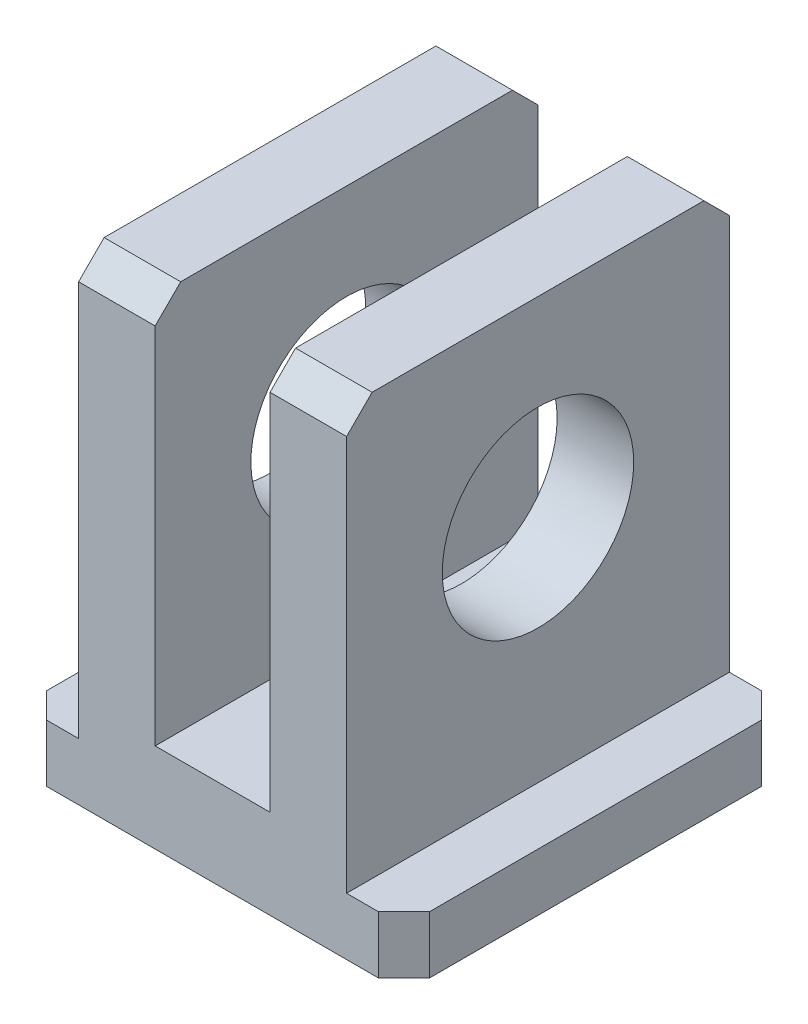
SolidWorks part; units mm, degrees
ref_plane "前视基准面" through (0, 0, 0) normal (0, 0, 1) x (1, 0, 0)
ref_plane "上视基准面" through (0, 0, 0) normal (0, 1, 0) x (1, 0, 0)
ref_plane "右视基准面" through (0, 0, 0) normal (1, 0, 0) x (0, 0, -1)
other "Configuration Table"
sketch "草图1" plane through (0, 0, 0) normal (0, 1, 0) x (1, 0, 0)
  line L0 (-15, 13) -> (-13, 15)
  line L1 (-13, -15) -> (13, -15)
  line L2 (-15, -13) -> (-15, 13)
  line L3 (-13, 15) -> (13, 15)
  line L4 (15, -13) -> (15, 13)
  line L5 (-15, -15) -> (15, 15) construction
  line L6 (-15, 15) -> (15, -15) construction
  line L7 (13, 15) -> (15, 13)
  line L8 (13, -15) -> (15, -13)
  line L9 (-15, -13) -> (-13, -15)
  point P0 (0, 0)
  dimension "D1" = 30
  dimension "D2" = 30
extrude "凸台-拉伸1" add sketch "草图1" along normal blind 4.5
sketch "草图2" plane through (15, 0, 0) normal (1, 0, 0) x (0, 0, -1)
  line L0 (-15, 4.5) -> (-15, 35.5)
  line L1 (-13, 37.5) -> (13, 37.5)
  line L2 (15, 4.5) -> (15, 35.5)
  line L3 (-15, 35.5) -> (-13, 37.5)
  line L4 (15, 35.5) -> (13, 37.5)
  line L5 (-15, 4.5) -> (15, 4.5)
  point P1 (-15, 37.5)
  point P5 (15, 37.5)
  dimension "D1" = 33
extrude "凸台-拉伸2" add sketch "草图2" against normal blind 30
sketch "草图3" plane through (0, 0, 15) normal (0, 0, 1) x (1, 0, 0)
  line L0 (-15, 4.5) -> (-10.5, 4.5)
  line L1 (-10.5, 4.5) -> (-10.5, 37.5)
  line L2 (-15, 37.5) -> (15, 37.5) construction
  line L3 (-15, 4.5) -> (-15, 37.5)
  line L4 (-15, 37.5) -> (-10.5, 37.5)
  line L5 (0, 0) -> (0, 29.372) construction
  line L6 (15, 4.5) -> (15, 37.5)
  line L7 (15, 4.5) -> (10.5, 4.5)
  line L8 (10.5, 4.5) -> (10.5, 37.5)
  line L9 (15, 37.5) -> (10.5, 37.5)
  line L10 (-4.5, 7) -> (4.5, 7)
  line L11 (4.5, 7) -> (4.5, 37.5)
  line L12 (4.5, 37.5) -> (-4.5, 37.5)
  line L14 (-4.5, 37.5) -> (-4.5, 7)
  line L15 (-13, 0) -> (13, 0) construction
  dimension "D1" = 4.5
  dimension "D2" = 9
  dimension "D3" = 7
extrude "切除-拉伸1" cut sketch "草图3" against normal blind 30
sketch "草图4" plane through (10.5, 0, 0) normal (1, 0, 0) x (0, 0, -1)
  line L0 (0, 0) -> (0, 14.1955) construction
  line L1 (-13, 0) -> (13, 0) construction
  circle A0 centre (0, 22.5) radius 7.5
  dimension "D1" = 15
  dimension "D2" = 22.5
extrude "切除-拉伸2" cut sketch "草图4" against normal blind 30
sketch "草图5" plane through (0, 0, 15) normal (0, 0, 1) x (1, 0, 0)
